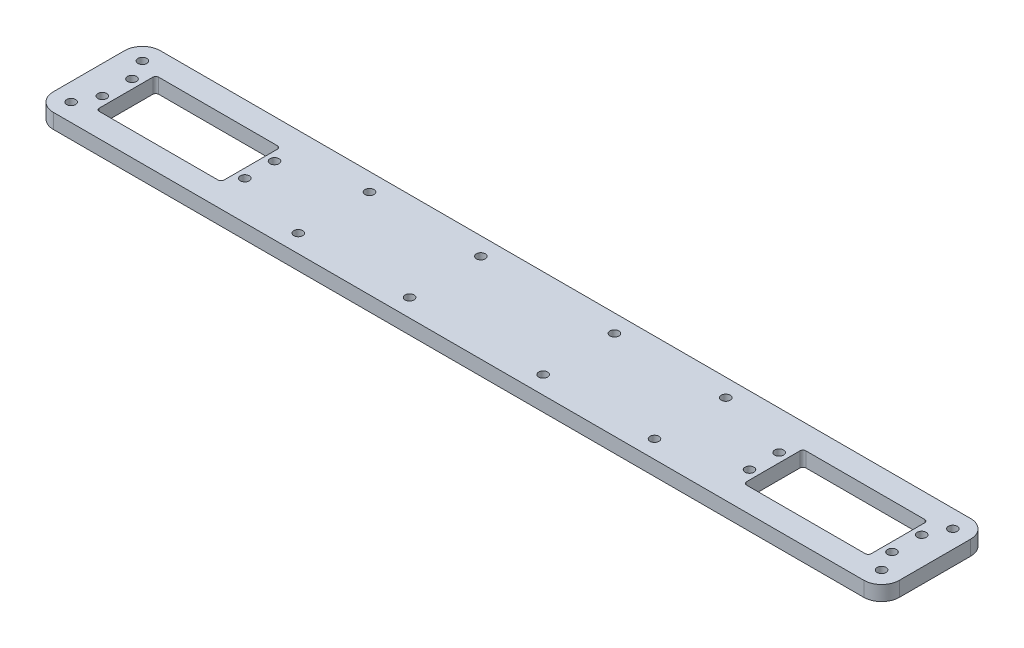
SolidWorks part; units mm, degrees
ref_plane "Front Plane" through (0, 0, 0) normal (0, 0, 1) x (1, 0, 0)
ref_plane "Top Plane" through (0, 0, 0) normal (0, 1, 0) x (1, 0, 0)
ref_plane "Right Plane" through (0, 0, 0) normal (1, 0, 0) x (0, 0, -1)
sketch "Sketch1" plane through (0, 0, 0) normal (0, 1, 0) x (1, 0, 0)
  line L0 (-142.5, 0) -> (142.5, 0) construction
  line L1 (-142.5, -18) -> (142.5, -18)
  line L2 (-142.5, -18) -> (-142.5, 18)
  line L3 (-142.5, 18) -> (142.5, 18)
  line L4 (142.5, -18) -> (142.5, 18)
  line L5 (-142.5, -18) -> (142.5, 18) construction
  line L6 (-142.5, 18) -> (142.5, -18) construction
  line L7 (0, 18) -> (0, -18) construction
  line L8 (-120, -10) -> (-120, 90.0595) construction
  line L9 (-130, 10) -> (-88, 10)
  line L10 (-130, 10) -> (-130, -10)
  line L11 (-130, -10) -> (-88, -10)
  line L12 (-88, 10) -> (-88, -10)
  line L13 (-130, 10) -> (-88, -10) construction
  line L14 (-130, -10) -> (-88, 10) construction
  line L15 (-133, -5) -> (-85, -5) construction
  line L16 (-133, -5) -> (-133, 5) construction
  line L17 (-133, 5) -> (-85, 5) construction
  line L18 (-85, -5) -> (-85, 5) construction
  line L19 (-133, -5) -> (-85, 5) construction
  line L20 (-133, 5) -> (-85, -5) construction
  line L21 (88, 10) -> (88, -10)
  line L22 (130, 10) -> (88, 10)
  line L23 (130, 10) -> (130, -10)
  line L24 (130, -10) -> (88, -10)
  line L25 (-22.5, -18) -> (-22.5, 18) construction
  line L26 (-28.5, 18) -> (-28.5, -18) construction
  line L27 (-136.5, 12) -> (-22.5, 12) construction
  circle A0 centre (-85, -5) radius 1.5
  circle A1 centre (-85, 5) radius 1.5
  circle A2 centre (-133, 5) radius 1.5
  circle A3 centre (-133, -5) radius 1.5
  circle A4 centre (133, -5) radius 1.5
  circle A5 centre (133, 5) radius 1.5
  circle A6 centre (85, -5) radius 1.5
  circle A7 centre (85, 5) radius 1.5
  circle A8 centre (-22.5, -12) radius 1.5
  circle A9 centre (-22.5, 12) radius 1.5
  circle A10 centre (-136.5, -12) radius 1.5
  circle A11 centre (-136.5, 12) radius 1.5
  circle A12 centre (22.5, -12) radius 1.5
  circle A13 centre (22.5, 12) radius 1.5
  circle A14 centre (136.5, -12) radius 1.5
  circle A15 centre (136.5, 12) radius 1.5
  circle A16 centre (-60, 12) radius 1.5
  circle A17 centre (-60, -12) radius 1.5
  circle A18 centre (60, -12) radius 1.5
  circle A19 centre (60, 12) radius 1.5
  point P0 (0, 0)
  point P10 (-109, 0)
  point P15 (-109, 0)
  dimension "D3" = 3
  dimension "D10" = 3
  dimension "D13" = 12
  dimension "D14" = 6
  dimension "D16" = 37.5
  dimension "D17" = 60
  dimension "D1" = 42
  dimension "D2" = 20
  dimension "D4" = 10
  dimension "D5" = 48
  dimension "D6" = 36
  dimension "D7" = 285
  dimension "D8" = 10
  dimension "D9" = 120
  dimension "D11" = 6
  dimension "D12" = 28.5
  dimension "D15" = 6
extrude "Boss-Extrude2" add sketch "Sketch1" along normal blind 5
fillet "Fillet1" radius 6 4 edges at (142.5, 2.5, 18) (142.5, 2.5, -18) (-142.5, 2.5, -18) (-142.5, 2.5, 18)
fillet "Fillet2" radius 1 8 edges at (-130, 2.5, -10) (-88, 2.5, -10) (-88, 2.5, 10) (-130, 2.5, 10) (88, 2.5, 10) (88, 2.5, -10) (130, 2.5, -10) (130, 2.5, 10)
